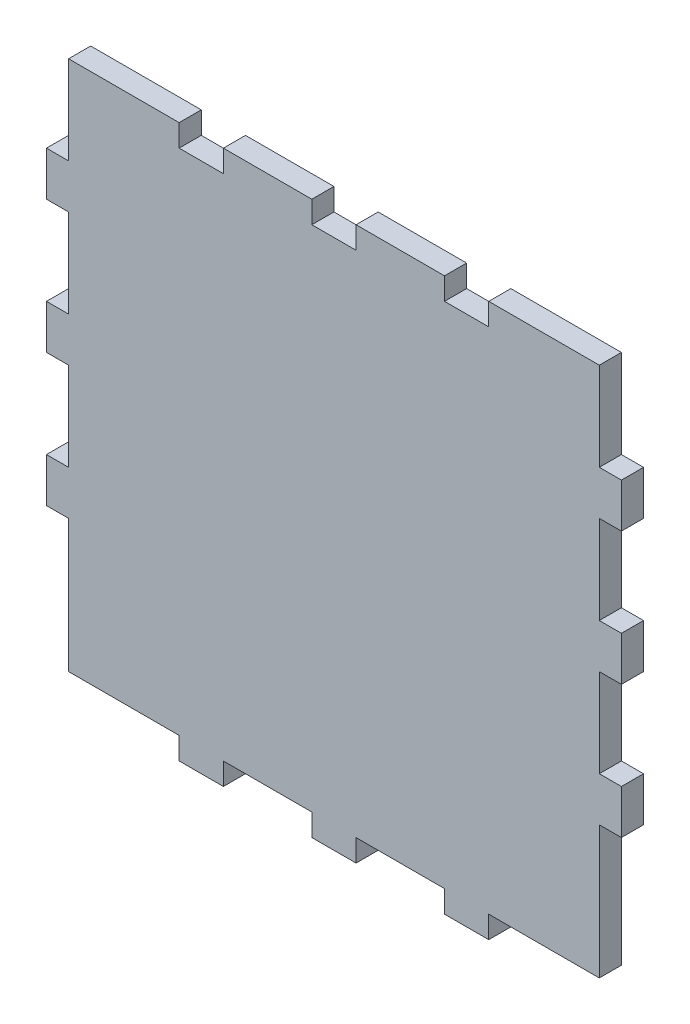
SolidWorks part; units mm, degrees
ref_plane "Ön Düzlem" through (0, 0, 0) normal (0, 0, 1) x (1, 0, 0)
ref_plane "Üst Düzlem" through (0, 0, 0) normal (0, 1, 0) x (1, 0, 0)
ref_plane "Sağ Düzlem" through (0, 0, 0) normal (1, 0, 0) x (0, 0, -1)
sketch "Sketch1" plane through (0, 0, 0) normal (0, 0, 1) x (1, 0, 0)
  line L0 (-35, 60) -> (-35, 55)
  line L1 (-60, -60) -> (-35, -60)
  line L2 (-60, -60) -> (-60, -30)
  line L3 (-60, 60) -> (-35, 60)
  line L4 (60, -60) -> (60, -30)
  line L5 (-60, -60) -> (60, 60) construction
  line L6 (-60, 60) -> (60, -60) construction
  line L7 (-35, 55) -> (-25, 55)
  line L8 (-25, 55) -> (-25, 60)
  line L15 (-5, 55) -> (5, 55)
  line L16 (-5, 60) -> (-5, 55)
  line L17 (5, 55) -> (5, 60)
  line L21 (25, 55) -> (35, 55)
  line L22 (25, 60) -> (25, 55)
  line L23 (35, 55) -> (35, 60)
  line L24 (-60, 40) -> (-65, 40)
  line L25 (-65, 40) -> (-65, 30)
  line L26 (-65, 30) -> (-60, 30)
  line L27 (60, 40) -> (65, 40)
  line L28 (65, 40) -> (65, 30)
  line L29 (65, 30) -> (60, 30)
  line L30 (-65, 10) -> (-65, 0)
  line L31 (-60, 10) -> (-65, 10)
  line L32 (-65, 0) -> (-60, 0)
  line L33 (65, 0) -> (60, 0)
  line L34 (65, 10) -> (65, 0)
  line L35 (60, 10) -> (65, 10)
  line L36 (-65, -20) -> (-65, -30)
  line L37 (-60, -20) -> (-65, -20)
  line L38 (-65, -30) -> (-60, -30)
  line L39 (65, -30) -> (60, -30)
  line L40 (65, -20) -> (65, -30)
  line L41 (60, -20) -> (65, -20)
  line L42 (-25, 60) -> (-5, 60)
  line L43 (5, 60) -> (25, 60)
  line L44 (35, 60) -> (60, 60)
  line L45 (35, -60) -> (60, -60)
  line L46 (5, -60) -> (25, -60)
  line L47 (-25, -60) -> (-5, -60)
  line L48 (-60, -20) -> (-60, 0)
  line L49 (-60, 10) -> (-60, 30)
  line L50 (60, -20) -> (60, 0)
  line L51 (60, 10) -> (60, 30)
  line L52 (60, 40) -> (60, 60)
  line L53 (-60, 40) -> (-60, 60)
  line L54 (-65, -80) -> (-65, -90) [skipped]
  line L55 (-60, -80) -> (-65, -80) [skipped]
  line L56 (-65, -90) -> (-60, -90) [skipped]
  line L57 (65, -90) -> (60, -90) [skipped]
  line L58 (65, -80) -> (65, -90) [skipped]
  line L59 (60, -80) -> (65, -80) [skipped]
  line L60 (65, -60) -> (60, -60) [skipped]
  line L61 (65, -50) -> (65, -60) [skipped]
  line L62 (60, -50) -> (65, -50) [skipped]
  line L63 (-60, -50) -> (-65, -50) [skipped]
  line L64 (-65, -50) -> (-65, -60) [skipped]
  line L65 (-65, -60) -> (-60, -60) [skipped]
  line L66 (-35, -60) -> (-35, -65)
  line L67 (-35, -65) -> (-25, -65)
  line L68 (-25, -65) -> (-25, -60)
  line L69 (5, -65) -> (5, -60)
  line L70 (-5, -65) -> (5, -65)
  line L71 (-5, -60) -> (-5, -65)
  line L72 (35, -65) -> (35, -60)
  line L73 (25, -65) -> (35, -65)
  line L74 (25, -60) -> (25, -65)
  point P0 (0, 0)
  point P20 (25.1432, -60)
  dimension "D1" = 120
  dimension "D2" = 25
  dimension "D3" = 5
  dimension "D4" = 10
  dimension "D6" = 20
  dimension "D7" = 5
  dimension "D8" = 10
  dimension "D9" = 20
  dimension "D11" = 20
  dimension "D12" = 120
  dimension "D13" = 10
  dimension "D14" = 5
  dimension "D15" = 25
  dimension "D17" = 20
  dimension "D5" = 3
  dimension "D10" = 5
  dimension "D16" = 3
extrude "Boss-Extrude1" add sketch "Sketch1" along normal blind 5
